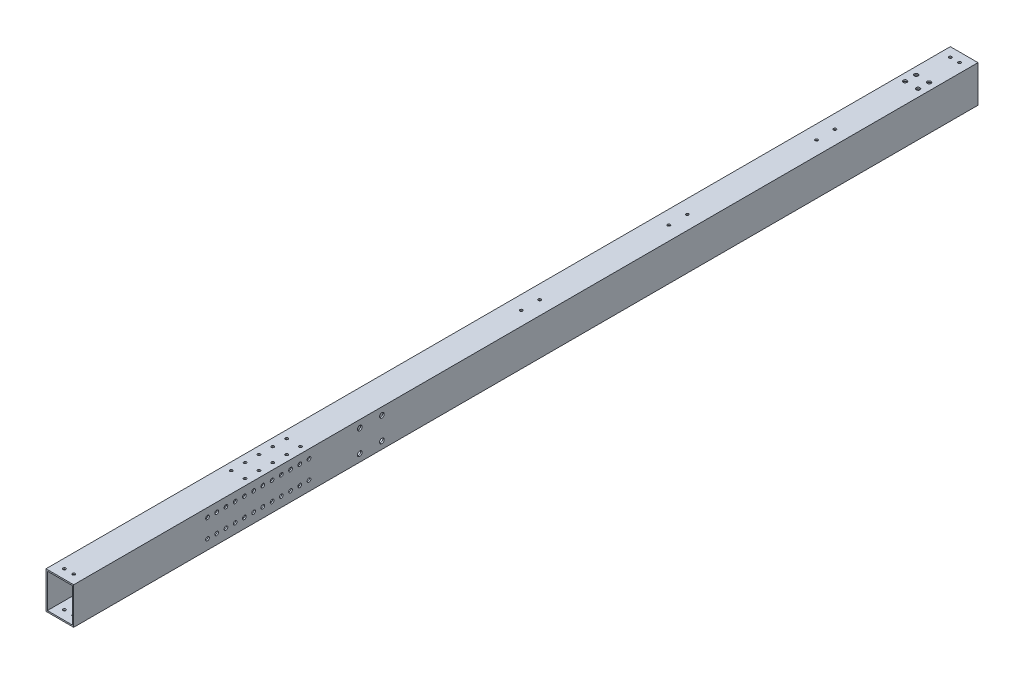
SolidWorks part; units mm, degrees
ref_plane "前视基准面" through (0, 0, 0) normal (0, 0, 1) x (1, 0, 0)
ref_plane "上视基准面" through (0, 0, 0) normal (0, 1, 0) x (1, 0, 0)
ref_plane "右视基准面" through (0, 0, 0) normal (1, 0, 0) x (0, 0, -1)
sketch "草图1" plane through (0, 0, 0) normal (0, 0, 1) x (1, 0, 0)
  line L0 (-13.5, 18.5) -> (13.5, 18.5)
  line L1 (-15, -20) -> (15, -20)
  line L2 (-15, -20) -> (-15, 20)
  line L3 (-15, 20) -> (15, 20)
  line L4 (15, -20) -> (15, 20)
  line L5 (-15, -20) -> (15, 20) construction
  line L6 (-15, 20) -> (15, -20) construction
  line L7 (13.5, -18.5) -> (13.5, 18.5)
  line L8 (-13.5, -18.5) -> (13.5, -18.5)
  line L9 (-13.5, -18.5) -> (-13.5, 18.5)
  point P0 (0, 0)
  dimension "D1" = 40
  dimension "D2" = 30
  dimension "D3" = 1.5
extrude "凸台-拉伸1" add sketch "草图1" along normal blind 980
sketch "草图2" plane through (0, 20, 0) normal (0, -1, 0) x (-1, 0, 0)
  line L0 (0, 0) -> (0, -50000) construction
  circle A0 centre (11, -65) radius 1.5
  circle A1 centre (-11, -65) radius 1.5
  circle A2 centre (11, -515) radius 1.5
  circle A3 centre (-11, -515) radius 1.5
  circle A4 centre (11, -105) radius 1.5
  circle A5 centre (-11, -105) radius 1.5
  dimension "D1" = 3
  dimension "D4" = 3
  dimension "D7" = 3
  dimension "D2" = 22
  dimension "D3" = 65
  dimension "D6" = 450
  dimension "D8" = 40
extrude "切除-拉伸1" [suppressed] cut sketch "草图2" along normal blind 1040
sketch "草图3" plane through (0, 20, 0) normal (0, -1, 0) x (-1, 0, 0)
  line L0 (0, 0) -> (0, -50000) construction
  line L2 (-16.5, -490) -> (49983.5, -490) construction
  line L3 (13.5, 0) -> (13.5, -980) construction
  line L4 (-13.5, 0) -> (-13.5, -980) construction
  line L5 (-15, 0) -> (15, 0) construction
  circle A0 centre (5, -10) radius 1.5
  circle A1 centre (-5, -10) radius 1.5
  circle A2 centre (-5, -970) radius 1.5
  circle A3 centre (5, -970) radius 1.5
  point P13 (13.5, -490)
  point P16 (-13.5, -490)
  dimension "D1" = 3
  dimension "D2" = 10
  dimension "D3" = 10
extrude "切除-拉伸2" cut sketch "草图3" along normal through all
sketch "草图4" plane through (0, 20, 0) normal (0, -1, 0) x (-1, 0, 0)
  line L1 (-8.2701, -787.5) -> (6.7299, -787.5) construction
  line L2 (-8.2701, -787.5) -> (-8.2701, -772.5) construction
  line L3 (-8.2701, -772.5) -> (6.7299, -772.5) construction
  line L4 (6.7299, -787.5) -> (6.7299, -772.5) construction
  line L5 (-8.2701, -787.5) -> (6.7299, -772.5) construction
  line L6 (-8.2701, -772.5) -> (6.7299, -787.5) construction
  line L7 (-0.7701, -780) -> (49999.2299, -780) construction
  line L8 (-0.7701, -840) -> (-0.7701, -50840) construction
  line L9 (15, -980) -> (-15, -980) construction
  circle A0 centre (-8.2701, -772.5) radius 1.5
  circle A1 centre (6.7299, -772.5) radius 1.5
  circle A2 centre (6.7299, -787.5) radius 1.5
  circle A3 centre (-8.2701, -787.5) radius 1.5
  point P0 (-0.7701, -780)
  dimension "D4" = 3
  dimension "D1" = 15
  dimension "D2" = 15
  dimension "D3" = 200
extrude "切除-拉伸3" cut sketch "草图4" along normal through all
sketch "草图5" plane through (0, 20, 0) normal (0, -1, 0) x (-1, 0, 0)
  line L0 (0, 0) -> (0, -50000) construction
  line L2 (0, -140) -> (0, -300) construction
  line L3 (0, -320) -> (0, -480) construction
  line L4 (15, 0) -> (-15, 0) construction
  circle A0 centre (0, -140) radius 1.5
  circle A1 centre (0, -160) radius 1.5
  circle A2 centre (0, -300) radius 1.5
  circle A3 centre (0, -320) radius 1.5
  circle A4 centre (0, -480) radius 1.5
  circle A5 centre (0, -460) radius 1.5
  dimension "D1" = 3
  dimension "D2" = 3
  dimension "D3" = 20
  dimension "D4" = 140
  dimension "D6" = 160
  dimension "D8" = 160
  dimension "D5" = 2
  dimension "D7" = 2
extrude "切除-拉伸4" cut sketch "草图5" along normal through all
sketch "草图8" plane through (0, -20, 0) normal (0, -1, 0) x (1, 0, 0)
  line L0 (0, 160) -> (0, 140) construction
  line L1 (7.5, 160) -> (7.5, 140)
  line L2 (-7.5, 160) -> (-7.5, 140)
  line L3 (0, 480) -> (0, 460) construction
  line L4 (7.5, 480) -> (7.5, 460)
  line L5 (-7.5, 480) -> (-7.5, 460)
  line L6 (0, 320) -> (0, 300) construction
  line L7 (7.5, 320) -> (7.5, 300)
  line L8 (-7.5, 320) -> (-7.5, 300)
  arc A0 (7.5, 160) -> (-7.5, 160) centre (0, 160) ccw
  arc A1 (-7.5, 140) -> (7.5, 140) centre (0, 140) ccw
  arc A2 (7.5, 480) -> (-7.5, 480) centre (0, 480) ccw
  arc A3 (-7.5, 460) -> (7.5, 460) centre (0, 460) ccw
  arc A4 (7.5, 320) -> (-7.5, 320) centre (0, 320) ccw
  arc A5 (-7.5, 300) -> (7.5, 300) centre (0, 300) ccw
  point P4 (0, 150)
  point P13 (0, 470)
  point P18 (0, 310)
  dimension "D1" = 7.5
  dimension "D2" = 7.5
  dimension "D3" = 7.5
extrude "切除-拉伸6" cut sketch "草图8" against normal blind 10
sketch "草图9" plane through (0, -20, 0) normal (0, -1, 0) x (1, 0, 0)
  circle A0 centre (-6.7299, 787.5) radius 3.25
  circle A1 centre (-6.7299, 772.5) radius 3.25
  circle A2 centre (8.2701, 772.5) radius 3.25
  circle A3 centre (8.2701, 787.5) radius 3.25
  dimension "D1" = 6.5
  dimension "D2" = 6.5
  dimension "D3" = 6.5
  dimension "D4" = 6.5
extrude "切除-拉伸7" cut sketch "草图9" against normal blind 10
pattern_linear "阵列(线性)1" count 4 spacing 15 along (0, 0, -1) of "切除-拉伸3", "切除-拉伸7"
sketch "草图10" plane through (-15, 0, 0) normal (-1, 0, 0) x (0, 0, 1)
  line L1 (0, 0) -> (664.4549, 0) construction
  line L2 (980, 20) -> (980, -20) construction
  circle A0 centre (646, 12) radius 2.55
  circle A1 centre (670, 12) radius 2.55
  circle A2 centre (646, -12) radius 2.55
  circle A3 centre (670, -12) radius 2.55
  dimension "D1" = 310
  dimension "D2" = 5.1
  dimension "D5" = 24
  dimension "D6" = 12
  dimension "D3" = 2
  dimension "D4" = 2
extrude "切除-拉伸8" cut sketch "草图10" against normal blind 51
sketch "草图11" plane through (-15, 0, 0) normal (-1, 0, 0) x (0, 0, 1)
  line L1 (980, 20) -> (980, -20) construction
  circle A0 centre (725, 10.6252) radius 2
  circle A1 centre (725, -9.3748) radius 2
  circle A2 centre (735, 10.6252) radius 2
  circle A3 centre (735, -9.3748) radius 2
  circle A4 centre (745, 10.6252) radius 2
  circle A5 centre (745, -9.3748) radius 2
  circle A6 centre (755, 10.6252) radius 2
  circle A7 centre (755, -9.3748) radius 2
  circle A8 centre (765, 10.6252) radius 2
  circle A9 centre (765, -9.3748) radius 2
  circle A10 centre (775, 10.6252) radius 2
  circle A11 centre (775, -9.3748) radius 2
  circle A12 centre (785, 10.6252) radius 2
  circle A13 centre (785, -9.3748) radius 2
  circle A14 centre (795, 10.6252) radius 2
  circle A15 centre (795, -9.3748) radius 2
  circle A16 centre (805, 10.6252) radius 2
  circle A17 centre (805, -9.3748) radius 2
  circle A18 centre (815, 10.6252) radius 2
  circle A19 centre (815, -9.3748) radius 2
  circle A20 centre (825, 10.6252) radius 2
  circle A21 centre (825, -9.3748) radius 2
  circle A22 centre (835, 10.6252) radius 2
  circle A23 centre (835, -9.3748) radius 2
  dimension "D1" = 4
  dimension "D2" = 2
  dimension "D4" = 145
  dimension "D3" = 12
extrude "切除-拉伸9" cut sketch "草图11" against normal blind 51
sketch "草图12" plane through (0, 20, 0) normal (0, 1, 0) x (1, 0, 0)
  line L0 (0, 0) -> (0, -98.6612) construction
  line L1 (15, 0) -> (-15, 0) construction
  circle A0 centre (-7, -45) radius 2.1
  circle A1 centre (-7, -57) radius 2.1
  circle A2 centre (7, -57) radius 2.1
  circle A3 centre (7, -45) radius 2.1
  dimension "D1" = 45
  dimension "D2" = 4.2
  dimension "D4" = 14
  dimension "D5" = 12
  dimension "D3" = 2
extrude "切除-拉伸10" cut sketch "草图12" against normal blind 10
sketch "草图13" plane through (0, -20, 0) normal (0, -1, 0) x (1, 0, 0)
  line L0 (0, 27.5) -> (0, 72.5) construction
  line L1 (-9, 27.5) -> (-9, 72.5)
  line L2 (9, 27.5) -> (9, 72.5)
  line L3 (-15, 0) -> (15, 0) construction
  arc A0 (-9, 27.5) -> (9, 27.5) centre (0, 27.5) ccw
  arc A1 (9, 72.5) -> (-9, 72.5) centre (0, 72.5) ccw
  point P3 (0, 50)
  dimension "D2" = 50
  dimension "D1" = 18
  dimension "D3" = 45
extrude "切除-拉伸11" cut sketch "草图13" against normal blind 10
equation "\"5。7\"=6"
